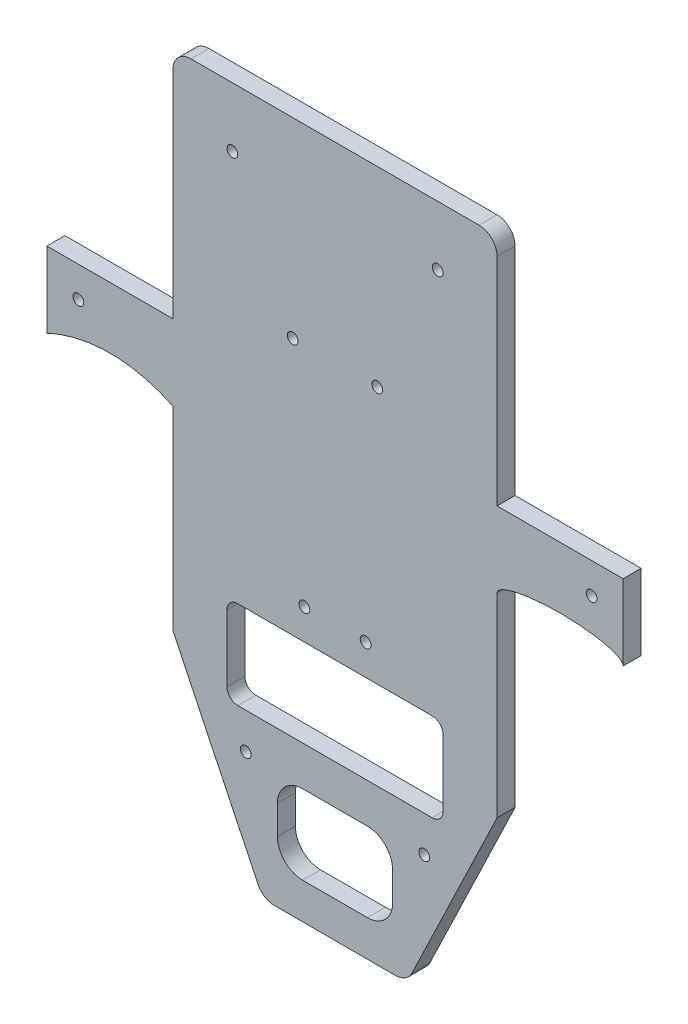
SolidWorks part; units mm, degrees
ref_plane "Front Plane" through (0, 0, 0) normal (0, 0, 1) x (1, 0, 0)
ref_plane "Top Plane" through (0, 0, 0) normal (0, 1, 0) x (1, 0, 0)
ref_plane "Right Plane" through (0, 0, 0) normal (1, 0, 0) x (0, 0, -1)
sketch "Sketch2" plane through (0, 0, 0) normal (0, 0, 1) x (1, 0, 0)
  line L0 (-45, -70) -> (-21.3623, -119.1665)
  line L2 (-45, -70) -> (-45, -16)
  line L3 (-40, 70) -> (40, 70)
  line L4 (45, -70) -> (45, -16)
  line L5 (-45, -70) -> (45, 70) construction
  line L6 (-45, 70) -> (45, -70) construction
  line L7 (-16.856, -122) -> (16.856, -122)
  line L8 (21.3623, -119.1665) -> (45, -70)
  line L9 (-45, -70) -> (45, -70) construction
  line L10 (80, -16) -> (-121.1118, -16) construction
  line L11 (-62.5, 5) -> (-62.5, -12) construction
  line L16 (-45, 5) -> (-45, 65)
  line L19 (45, 5) -> (80, 5)
  line L20 (80, -16) -> (80, 5)
  line L23 (-45, 5) -> (-80, 5)
  line L24 (-80, -16) -> (-80, 5)
  line L25 (45, 5) -> (45, 65)
  line L26 (62.5, -12) -> (-123.4654, -12) construction
  line L27 (-80, 1.8944) -> (-45, 1.8944) construction
  arc A0 (16.856, -122) -> (21.3623, -119.1665) centre (16.856, -117) ccw
  arc A1 (-21.3623, -119.1665) -> (-16.856, -122) centre (-16.856, -117) ccw
  arc A2 (40, 70) -> (45, 65) centre (40, 65) cw
  arc A3 (-45, 65) -> (-40, 70) centre (-40, 65) cw
  ellipse E0 centre (-62.5, -52.2183) end of major axis (-80, -88.4366) minor radius 40.2246 (-45, -16) -> (-80, -16) ccw
  ellipse E1 centre (62.5, -16) end of major axis (45, -16) minor radius 4 (80, -16) -> (45, -16) ccw
  point P0 (0, 0)
  point P30 (16, -92)
  point P33 (-16, -92)
  point P44 (-62.5, -48.0012)
  dimension "D13" = 65
  dimension "D7" = 5
  dimension "D1" = 90
  dimension "D2" = 140
  dimension "D3" = 52
  dimension "D6" = 32
  dimension "D8" = 65
  dimension "D9" = 35
  dimension "D10" = 21
  dimension "D11" = 35
  dimension "D12" = 21
  dimension "D14" = 54
  dimension "D15" = 140
extrude "Boss-Extrude1" add sketch "Sketch2" along normal blind 5 contours L25 A2 L3 A3 L16 L23 L24 E0 L2 L0 A1 L7 A0 L8 L4 E1 L20 L19
sketch "Sketch3" plane through (0, 0, 5) normal (0, 0, 1) x (1, 0, 0)
  line L0 (-45, 5) -> (-45, -16) construction
  line L1 (-62.5, 5) -> (-62.5, -11.9937) construction
  line L2 (-45, 5) -> (-80, 5) construction
  line L3 (-62.5, -3.4969) -> (-80, -3.4969) construction
  line L4 (-80, -16) -> (-80, 5) construction
  line L5 (45, 5) -> (45, -16) construction
  line L6 (62.5, 5) -> (62.5, -12) construction
  line L7 (45, 5) -> (80, 5) construction
  line L8 (62.5, -3.5) -> (80, -3.5) construction
  line L9 (80, -16) -> (80, 5) construction
  arc A0 (-45, -16) -> (-80, -16) centre (-62.5, -52.2183) ccw construction
  circle A1 centre (-71.25, -3.4969) radius 1.5
  circle A2 centre (71.25, -3.5) radius 1.5
  ellipse E0 centre (62.5, -16) end of major axis (80, -16) minor radius 4 (80, -16) -> (45, -16) ccw construction
extrude "Cut-Extrude1" cut sketch "Sketch3" against normal through all
sketch "Sketch4" plane through (0, 0, 5) normal (0, 0, 1) x (1, 0, 0)
  line L0 (-16.856, -122) -> (16.856, -122) construction
  line L1 (-9, -90) -> (9, -90)
  line L2 (-16, -97) -> (-16, -105)
  line L3 (-9, -112) -> (9, -112)
  line L4 (16, -97) -> (16, -105)
  line L5 (-45, -70) -> (45, -70) construction
  arc A0 (9, -112) -> (16, -105) centre (9, -105) ccw
  arc A1 (-16, -105) -> (-9, -112) centre (-9, -105) ccw
  arc A2 (-9, -90) -> (-16, -97) centre (-9, -97) ccw
  arc A3 (9, -90) -> (16, -97) centre (9, -97) cw
  point P10 (0, -70)
  point P11 (0, -90)
  point P18 (-16, -90)
  point P21 (16, -90)
  dimension "D5" = 7
  dimension "D1" = 32
  dimension "D2" = 10
  dimension "D3" = 20
  dimension "D4" = 0
extrude "Cut-Extrude2" cut sketch "Sketch4" against normal through all
sketch "Sketch5" plane through (0, 0, 5) normal (0, 0, 1) x (1, 0, 0)
  line L0 (-11.725, 70) -> (-11.725, 15.45) construction
  line L1 (-40, 70) -> (40, 70) construction
  line L2 (-10.225, 16.95) -> (10.225, 16.95) construction
  line L3 (0, 70) -> (0, 23.3022)
  line L4 (-45, 5) -> (-45, 65) construction
  line L5 (45, 5) -> (45, 65) construction
  circle A0 centre (-11.725, 16.95) radius 1.5
  circle A1 centre (11.725, 16.95) radius 1.5
  dimension "D1" = 1.5
  dimension "D2" = 3
  dimension "D3" = 3
  dimension "D7" = 33.275
  dimension "D4" = 20.45
  dimension "D5" = 45
  dimension "D6" = 33.275
extrude "Cut-Extrude3" cut sketch "Sketch5" against normal through all contours A1 | A0
sketch "Sketch6" plane through (0, 0, 5) normal (0, 0, 1) x (1, 0, 0)
  line L0 (-11.725, 15.45) -> (-50.0442, 15.45) construction
  line L1 (-45, 5) -> (-80, 5) construction
  line L2 (-45, -70) -> (45, -70) construction
  line L3 (0, -70) -> (0, -90) construction
  line L4 (9, -90) -> (-9, -90) construction
  line L5 (-30, -62.263) -> (30, -62.263) construction
  line L6 (-27, -54.5) -> (27, -54.5)
  line L7 (-30, -57.5) -> (-30, -76)
  line L8 (-27, -79) -> (27, -79)
  line L9 (30, -57.5) -> (30, -76)
  circle A0 centre (-11.725, 16.95) radius 1.5 construction
  arc A1 (27, -79) -> (30, -76) centre (27, -76) ccw
  arc A2 (-30, -76) -> (-27, -79) centre (-27, -76) ccw
  arc A3 (-27, -54.5) -> (-30, -57.5) centre (-27, -57.5) ccw
  arc A4 (27, -54.5) -> (30, -57.5) centre (27, -57.5) cw
  point P20 (0, -54.5)
  point P23 (30, -79)
  point P28 (-30, -54.5)
  point P31 (30, -54.5)
  dimension "D7" = 3
  dimension "D1" = 10.45
  dimension "D2" = 24.5
  dimension "D3" = 11
  dimension "D4" = 60
  dimension "D5" = 15.5
  dimension "D6" = 0
extrude "Cut-Extrude4" cut sketch "Sketch6" against normal through all contours L7 A2 L8 A1 L9 A4 L6 A3
sketch "Sketch7" plane through (0, 0, 5) normal (0, 0, 1) x (1, 0, 0)
  line L0 (-27, -54.5) -> (27, -54.5) construction
  line L1 (-9.9385, -54.5) -> (-9.9385, -46.4253) construction
  line L2 (-40, 70) -> (40, 70) construction
  line L3 (-45, 5) -> (-45, 65) construction
  line L4 (45, 5) -> (45, 65) construction
  line L5 (-27, -79) -> (27, -79) construction
  line L6 (-45, -70) -> (-21.3623, -119.1665) construction
  line L7 (21.3623, -119.1665) -> (45, -70) construction
  line L8 (-7, -46) -> (7, -46) construction
  line L9 (45, -70) -> (45, -16) construction
  line L10 (-45, -70) -> (-45, -16) construction
  line L11 (-8.5, -47.5) -> (8.5, -47.5) construction
  circle A0 centre (-28.5, 53.5) radius 1.5
  circle A1 centre (28.5, 53.5) radius 1.5
  circle A2 centre (-24.7697, -89) radius 1.5
  circle A3 centre (24.7697, -89) radius 1.5
  circle A4 centre (-8.5, -46) radius 1.5
  circle A5 centre (8.5, -46) radius 1.5
  point P30 (0, -54.5)
  point P31 (0, -46)
  dimension "D1" = 16.5
  dimension "D6" = 10
  dimension "D10" = 0
  dimension "D12" = 3
  dimension "D13" = 3
  dimension "D14" = 36.5
  dimension "D2" = 16.5
  dimension "D3" = 16.5
  dimension "D4" = 16.5
  dimension "D5" = 16.5
  dimension "D7" = 10
  dimension "D8" = 10
  dimension "D9" = 10
  dimension "D11" = 14
  dimension "D15" = 35.0615
  dimension "D16" = 7
extrude "Cut-Extrude5" cut sketch "Sketch7" against normal through all
